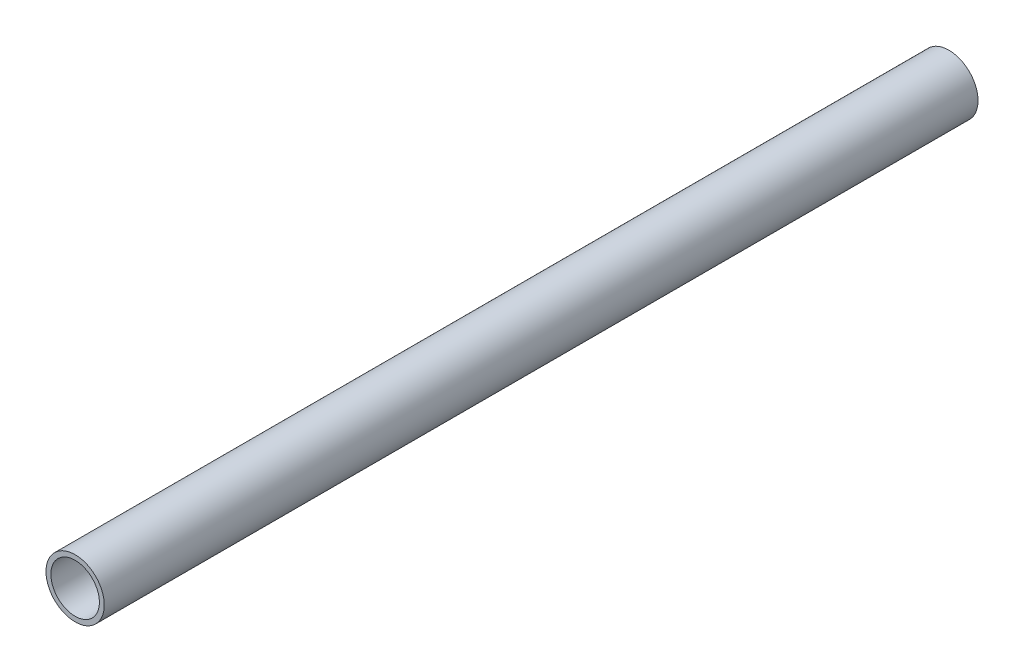
SolidWorks part; units mm, degrees
ref_plane "Alzado" through (0, 0, 0) normal (0, 0, 1) x (1, 0, 0)
ref_plane "Planta" through (0, 0, 0) normal (0, 1, 0) x (1, 0, 0)
ref_plane "Vista lateral" through (0, 0, 0) normal (1, 0, 0) x (0, 0, -1)
sketch "Croquis1" plane through (0, 0, 0) normal (0, 0, 1) x (1, 0, 0)
  circle A0 centre (0, 0) radius 6
  circle A1 centre (0, 0) radius 5
  dimension "D1" = 12
  dimension "D2" = 1
extrude "Saliente-Extruir1" add sketch "Croquis1" along normal mid plane 180
